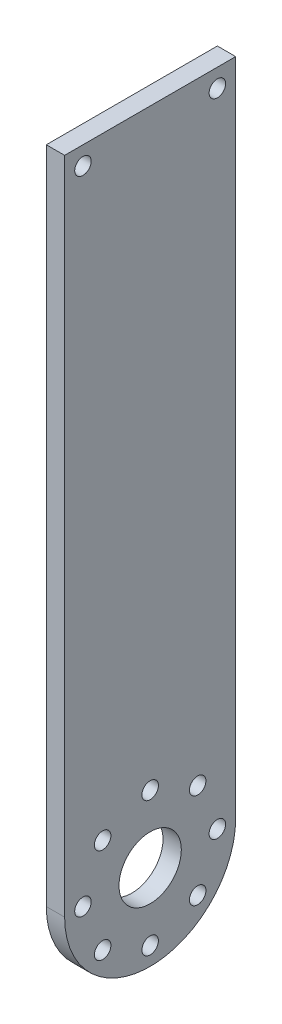
SolidWorks part; units mm, degrees
ref_plane "前视基准面" through (0, 0, 0) normal (0, 0, 1) x (1, 0, 0)
ref_plane "上视基准面" through (0, 0, 0) normal (0, 1, 0) x (1, 0, 0)
ref_plane "右视基准面" through (0, 0, 0) normal (1, 0, 0) x (0, 0, -1)
sketch "草图1" plane through (0, 0, 0) normal (1, 0, 0) x (0, 0, -1)
  line L0 (0, -82.9043) -> (0, 247.7263) construction
  line L1 (-14, 0) -> (-14, 108)
  line L2 (-14, 108) -> (14, 108)
  line L3 (14, 0) -> (14, 108)
  arc A0 (-14, 0) -> (14, 0) centre (0, 0) ccw
  circle A1 centre (0, -11) radius 1.35
  circle A2 centre (-7.7782, -7.7782) radius 1.35
  circle A3 centre (-11, 0) radius 1.35
  circle A4 centre (-7.7782, 7.7782) radius 1.35
  circle A5 centre (0, 11) radius 1.35
  circle A6 centre (7.7782, 7.7782) radius 1.35
  circle A7 centre (11, 0) radius 1.35
  circle A8 centre (7.7782, -7.7782) radius 1.35
  circle A9 centre (0, 0) radius 5.1
  circle A10 centre (-11, 105) radius 1.35
  circle A11 centre (11, 105) radius 1.35
  point P28 (0, 0)
  dimension "D1" = 28
  dimension "D6" = 11
  dimension "D9" = 11
  dimension "D10" = 3
  dimension "D5" = 2.7
  dimension "D7" = 10.2
  dimension "D8" = 2.7
  dimension "D2" = 105
extrude "凸台-拉伸1" add sketch "草图1" along normal blind 3
